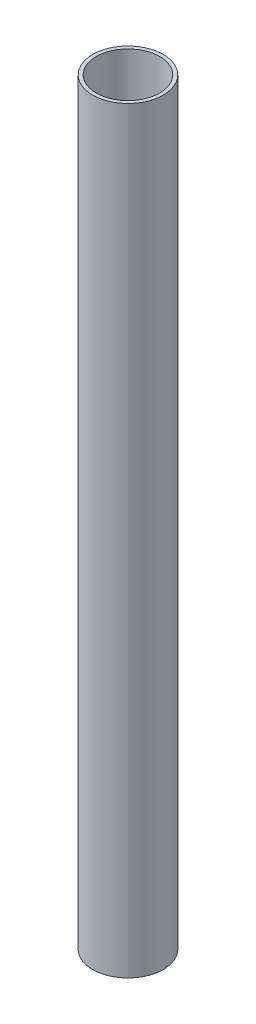
SolidWorks part; units mm, degrees
material "Thornel VCB-20 Carbon Cloth"
ref_plane "Front Plane" through (0, 0, 0) normal (0, 0, 1) x (1, 0, 0)
ref_plane "Top Plane" through (0, 0, 0) normal (0, 1, 0) x (1, 0, 0)
ref_plane "Right Plane" through (0, 0, 0) normal (1, 0, 0) x (0, 0, -1)
sketch "Sketch1" plane through (0, 0, 0) normal (0, 1, 0) x (1, 0, 0)
  circle A0 centre (0, 0) radius 10
  circle A1 centre (0, 0) radius 9
  dimension "D1" = 18
  dimension "D2" = 20
extrude "Boss-Extrude1" add sketch "Sketch1" along normal blind 215
